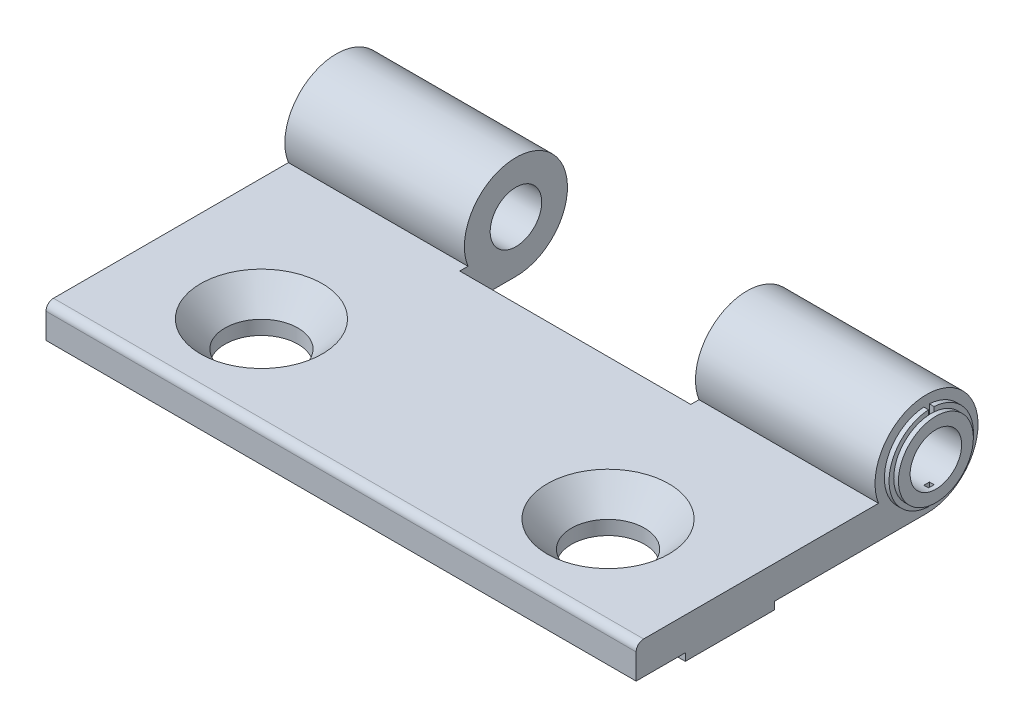
SolidWorks part; units mm, degrees
ref_plane "Front Plane" through (0, 0, 0) normal (0, 0, 1) x (1, 0, 0)
ref_plane "Top Plane" through (0, 0, 0) normal (0, 1, 0) x (1, 0, 0)
ref_plane "Right Plane" through (0, 0, 0) normal (1, 0, 0) x (0, 0, -1)
ref_plane "Plane1" through (-12.3333, 0, 0) normal (1, 0, 0) x (0, 0, -1)
sketch "Sketch1" plane through (-12.3333, 0, 0) normal (1, 0, 0) x (0, 0, -1)
  line L0 (-5.1235, 3.5) -> (-5.1235, 0)
  line L1 (-5.1235, 0) -> (0, 0)
  arc A0 (0, 0) -> (-5.1235, 3.5) centre (0, 5.5) ccw
extrude "Boss-Extrude1" add sketch "Sketch1" against normal blind 19.1667
sketch "Sketch2" plane through (-31.5, 0, 0) normal (-1, 0, 0) x (0, 0, 1)
  line L0 (-0.3, 9.99) -> (-0.3, 8.2336)
  line L1 (0.3, 8.2336) -> (0.3, 9.99)
  line L2 (0.3, 1.01) -> (0.3, 2.7664)
  line L3 (-0.3, 2.7664) -> (-0.3, 1.01)
  arc A0 (-0.3, 1.01) -> (-0.3, 9.99) centre (0, 5.5) cw
  arc A1 (-0.3, 8.2336) -> (0.3, 8.2336) centre (0, 5.5) cw
  arc A2 (0.3, 9.99) -> (0.3, 1.01) centre (0, 5.5) cw
  arc A3 (0.3, 2.7664) -> (-0.3, 2.7664) centre (0, 5.5) cw
extrude "Boss-Extrude2" add sketch "Sketch2" along normal blind 0.5
sketch "Sketch3" plane through (-12.3333, 0, 0) normal (1, 0, 0) x (0, 0, -1)
  line L0 (-5.1235, 3.5) -> (0, 3.5)
  line L1 (0, 3.5) -> (0, 0)
  line L2 (0, 0) -> (-5.1235, 0)
  line L3 (-5.1235, 0) -> (-5.1235, 3.5)
extrude "Boss-Extrude3" add sketch "Sketch3" along normal blind 24.6667
sketch "Sketch4" plane through (12.3333, 0, 0) normal (1, 0, 0) x (0, 0, -1)
  line L0 (-1.8875, 3.5) -> (0, 3.5)
  line L1 (0, 3.5) -> (0, 2.75)
  line L2 (0, 0) -> (-5.1235, 0)
  line L3 (-5.1235, 0) -> (-5.1235, 3.5)
  arc A0 (0, 2.75) -> (-1.8875, 3.5) centre (0, 5.5) ccw
  arc A1 (-5.1235, 3.5) -> (0, 0) centre (0, 5.5) cw
extrude "Boss-Extrude4" add sketch "Sketch4" along normal blind 19.1667
sketch "Sketch5" plane through (31.5, 0, 0) normal (1, 0, 0) x (0, 0, -1)
  line L0 (-0.3, 9.99) -> (-0.3, 8.2336)
  line L1 (-0.3, 2.7664) -> (-0.3, 1.01)
  arc A0 (-0.3, 1.01) -> (-0.3, 9.99) centre (0, 5.5) cw
  arc A1 (-0.3, 8.2336) -> (-0.3, 2.7664) centre (0, 5.5) ccw
extrude "Boss-Extrude5" add sketch "Sketch5" along normal blind 0.5
sketch "Sketch6" plane through (31.5, 0, 0) normal (1, 0, 0) x (0, 0, -1)
  line L0 (0.3, 1.01) -> (0.3, 2.7664)
  line L1 (0.3, 8.2336) -> (0.3, 9.99)
  arc A0 (0.3, 9.99) -> (0.3, 1.01) centre (0, 5.5) cw
  arc A1 (0.3, 2.7664) -> (0.3, 8.2336) centre (0, 5.5) ccw
extrude "Boss-Extrude6" add sketch "Sketch6" along normal blind 0.5
sketch "Sketch7" plane through (31.5, 0, 0) normal (1, 0, 0) x (0, 0, -1)
  line L0 (0, 3.5) -> (-1.8875, 3.5)
  line L1 (0, 2.75) -> (0, 3.5)
  arc A0 (-1.8875, 3.5) -> (0, 2.75) centre (0, 5.5) ccw
extrude "Cut-Extrude1" cut sketch "Sketch7" against normal blind 19.1667
sketch "Sketch8" plane through (0, 0, 5.1235) normal (0, 0, 1) x (1, 0, 0)
  line L0 (-31.5, 0) -> (-31.5, 3.5)
  line L1 (-31.5, 3.5) -> (31.5, 3.5)
  line L2 (31.5, 3.5) -> (31.5, 0)
  line L3 (31.5, 0) -> (-31.5, 0)
extrude "Boss-Extrude7" add sketch "Sketch8" along normal blind 0.3383
sketch "Sketch9" plane through (0, 0, 0) normal (0, -1, 0) x (1, 0, 0)
  line L0 (31.5, 5.4618) -> (31.5, 0)
  line L1 (31.5, 0) -> (-31.5, 0)
  line L2 (-31.5, 0) -> (-31.5, 5.4618)
  line L3 (-31.5, 5.4618) -> (31.5, 5.4618)
extrude "Boss-Extrude8" add sketch "Sketch9" along normal blind 0.8
sketch "Sketch10" plane through (0, 0, 0) normal (0, 0, -1) x (-1, 0, 0)
  line L0 (12.3333, 3.5) -> (-12.3333, 3.5)
  line L1 (-12.3333, 3.5) -> (-12.3333, 0)
  line L2 (-12.3333, 0) -> (-31.5, 0)
  line L3 (-31.5, 0) -> (-31.5, -0.8)
  line L4 (-31.5, -0.8) -> (31.5, -0.8)
  line L5 (31.5, -0.8) -> (31.5, 0)
  line L6 (31.5, 0) -> (12.3333, 0)
  line L7 (12.3333, 0) -> (12.3333, 3.5)
extrude "Cut-Extrude2" cut sketch "Sketch10" against normal blind 5.1235
sketch "Sketch11" plane through (0, 0, 5.4618) normal (0, 0, 1) x (1, 0, 0)
  line L0 (-31.5, -0.8) -> (-31.5, 3.5)
  line L1 (-31.5, 3.5) -> (31.5, 3.5)
  line L2 (31.5, 3.5) -> (31.5, -0.8)
  line L3 (31.5, -0.8) -> (-31.5, -0.8)
extrude "Boss-Extrude9" add sketch "Sketch11" along normal blind 25.5382
sketch "Sketch12" plane through (0, 0, 5.1235) normal (0, 0, -1) x (-1, 0, 0)
  line L0 (12.3333, 3.5) -> (-12.3333, 3.5)
  line L1 (-12.3333, 3.5) -> (-12.3333, 0)
  line L2 (-12.3333, 0) -> (-31.5, 0)
  line L3 (-31.5, 0) -> (-31.5, -0.8)
  line L4 (-31.5, -0.8) -> (31.5, -0.8)
  line L5 (31.5, -0.8) -> (31.5, 0)
  line L6 (31.5, 0) -> (12.3333, 0)
  line L7 (12.3333, 0) -> (12.3333, 3.5)
extrude "Cut-Extrude3" cut sketch "Sketch12" against normal blind 0.3383
sketch "Sketch13" plane through (0, 0, 5.4618) normal (0, 0, -1) x (-1, 0, 0)
  line L0 (31.5, -0.8) -> (31.5, 0)
  line L1 (31.5, 0) -> (-31.5, 0)
  line L2 (-31.5, 0) -> (-31.5, -0.8)
  line L3 (-31.5, -0.8) -> (31.5, -0.8)
extrude "Cut-Extrude4" cut sketch "Sketch13" against normal blind 10.7882
sketch "Sketch14" plane through (0, 0, 5.4618) normal (0, 0, -1) x (-1, 0, 0)
  line L0 (12.3333, 3.5) -> (-12.3333, 3.5)
  line L1 (-12.3333, 3.5) -> (-12.3333, 0)
  line L2 (-12.3333, 0) -> (12.3333, 0)
  line L3 (12.3333, 0) -> (12.3333, 3.5)
extrude "Cut-Extrude5" cut sketch "Sketch14" against normal blind 0.5382
sketch "Sketch15" plane through (32, 0, 0) normal (1, 0, 0) x (0, 0, -1)
  circle A0 centre (0, 5.5) radius 4
  circle A1 centre (0, 5.5) radius 2.75
extrude "Boss-Extrude10" add sketch "Sketch15" along normal blind 0.5
sketch "Sketch16" plane through (-32, 0, 0) normal (-1, 0, 0) x (0, 0, 1)
  circle A0 centre (0, 5.5) radius 4
extrude "Boss-Extrude11" add sketch "Sketch16" along normal blind 0.5
sketch "Sketch17" plane through (31.5, 0, 0) normal (1, 0, 0) x (0, 0, -1)
  line L0 (-31, -0.8) -> (-25.75, -0.8)
  line L1 (-25.75, -0.8) -> (-25.75, 0)
  line L2 (-25.75, 0) -> (-31, 0)
  line L3 (-31, 0) -> (-31, -0.8)
extrude "Cut-Extrude6" cut sketch "Sketch17" against normal through all
hole_wizard "#10 Clearance Hole1" positions "Sketch19" profile "Sketch18" hole size "#10" standard "ANSI Inch"
sketch "Sketch19" plane through (-32.5, 0, 0) normal (-1, 0, 0) x (0, 0, 1)
  point P0 (0, 5.5)
sketch "Sketch18" plane through (-32.5, 5.5, 0) normal (0, 1, 0) x (0, 0, 1)
  line L0 (0, 0) -> (0, 20.1667)
  line L1 (0, 20.1667) -> (2.75, 20.1667)
  line L2 (2.75, 20.1667) -> (2.75, 0)
  line L5 (2.75, 0) -> (0, 0)
  line L10 (0, 20.1667) -> (-2.75, 20.1667) construction
  line L11 (0, -6.35) -> (0, 107.95) construction
  dimension "Hole Dia." = 5.5
  dimension "Hole Depth" = 20.1667
  dimension "Drill Angle" = 180
hole_wizard "Hole1" positions "Sketch21" profile "Sketch20" legacy
sketch "Sketch21" plane through (0, 3.5, 0) normal (0, 1, 0) x (1, 0, 0)
  point P0 (18.5, -21)
  point P1 (-18.5, -21)
sketch "Sketch20" plane through (18.5, 3.5, 21) normal (1, 0, 0) x (0, 0, 1)
  line L0 (0, 0) -> (0, 4.3)
  line L1 (0, 4.3) -> (3.9, 4.3)
  line L2 (3.9, 4.3) -> (3.9, 2.8)
  line L3 (3.9, 2.8) -> (6.5, 0)
  line L4 (6.5, 0) -> (0, 0)
  line L5 (0, -6.4453) -> (0, 115.525) construction
  line L6 (-3.9, 2.8) -> (-6.5, 0) construction
  dimension "Diameter" = 7.8
  dimension "Depth" = 4.3
  dimension "C-Sink Angle" = 85.758
  dimension "C-Sink Diameter" = 13
fillet "Fillet1" radius 0.8 1 edges at (0, 3.5, 31)
scale "Scale1" scale about centroid uniform scaling yes scale factor 0.3333
sketch "Sketch22" plane through (0, 3.0641, 0) normal (0, 1, 0) x (1, 0, 0)
  circle A0 centre (6.1661, -14.8798) radius 0.8499
